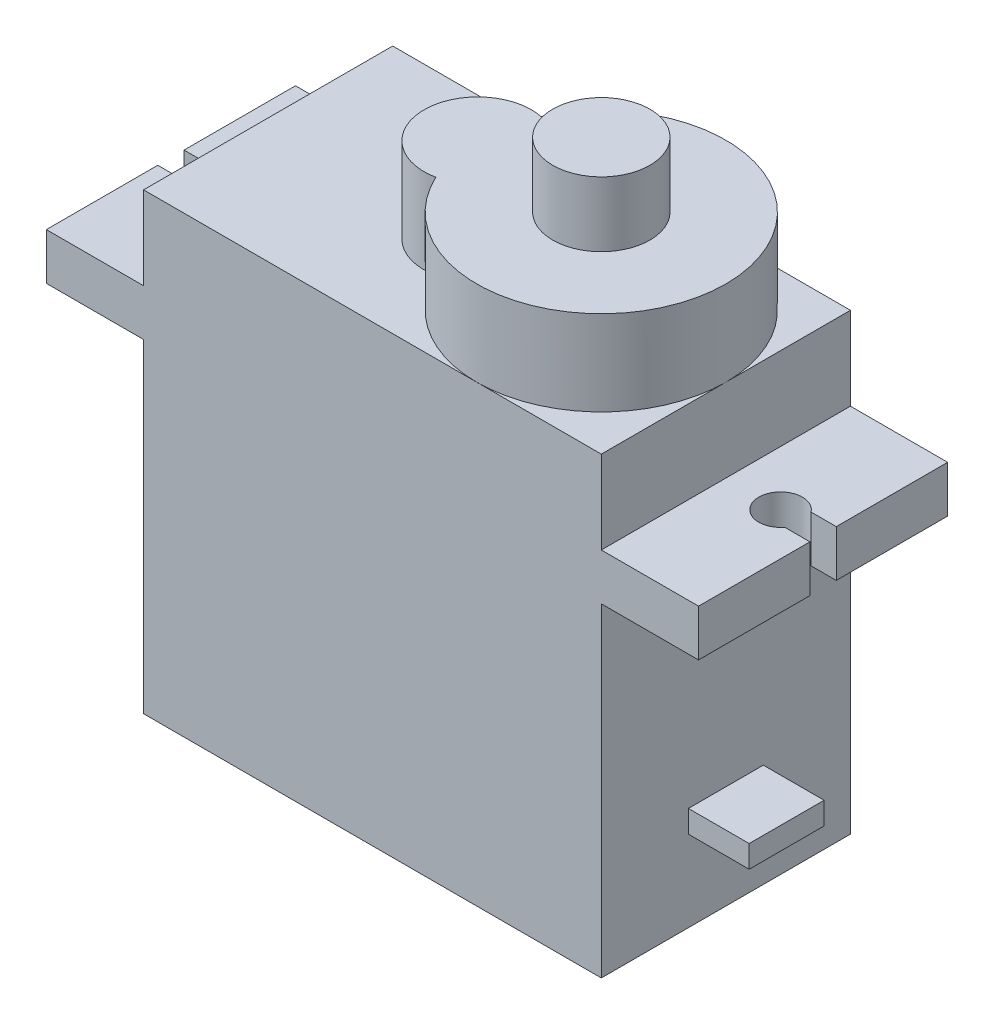
SolidWorks part; units mm, degrees
ref_plane "Plano frontal" through (0, 0, 0) normal (0, 0, 1) x (1, 0, 0)
ref_plane "Plano superior" through (0, 0, 0) normal (0, 1, 0) x (1, 0, 0)
ref_plane "Plano direito" through (0, 0, 0) normal (1, 0, 0) x (0, 0, -1)
sketch "Esboço1" plane through (0, 0, 0) normal (0, 1, 0) x (1, 0, 0)
  line L1 (-11.3, -6.15) -> (11.3, -6.15)
  line L2 (-11.3, -6.15) -> (-11.3, 6.15)
  line L3 (-11.3, 6.15) -> (11.3, 6.15)
  line L4 (11.3, -6.15) -> (11.3, 6.15)
  line L5 (-11.3, -6.15) -> (11.3, 6.15) construction
  line L6 (-11.3, 6.15) -> (11.3, -6.15) construction
  point P0 (0, 0)
  dimension "D1" = 22.6
  dimension "D2" = 12.3
extrude "Ressalto-extrusão1" add sketch "Esboço1" along normal blind 22.4
sketch "Esboço2" plane through (11.3, 0, 0) normal (1, 0, 0) x (0, 0, -1)
  line L0 (-6.15, 22.4) -> (-6.15, 0) construction
  line L1 (-6.15, 18.3) -> (6.15, 18.3)
  line L2 (-6.15, 18.3) -> (-6.15, 16)
  line L3 (-6.15, 16) -> (6.15, 16)
  line L4 (6.15, 18.3) -> (6.15, 16)
  line L5 (6.15, 22.4) -> (6.15, 0) construction
  line L6 (-6.15, 0) -> (6.15, 0) construction
  dimension "D1" = 2.3
  dimension "D2" = 16
extrude "Ressalto-extrusão2" add sketch "Esboço2" along normal blind 4.8
sketch "Esboço3" plane through (0, 18.3, 0) normal (0, 1, 0) x (1, 0, 0)
  line L0 (14.8562, 0.65) -> (16.1, 0.65)
  line L1 (16.1, 6.15) -> (16.1, -6.15) construction
  line L2 (14.8562, -0.65) -> (16.1, -0.65)
  line L3 (16.1, 0.65) -> (16.1, -0.65)
  arc A0 (14.8562, 0.65) -> (14.8562, -0.65) centre (14, 0) ccw
  dimension "D2" = 2.15
  dimension "D3" = 2.1
  dimension "D1" = 1.3
extrude "Corte-extrusão1" cut sketch "Esboço3" against normal through all
mirror "Espelhar1" about plane through (0, 0, 0) normal (1, 0, 0) of "Ressalto-extrusão2", "Corte-extrusão1"
sketch "Esboço4" plane through (0, 22.4, 0) normal (0, 1, 0) x (1, 0, 0)
  line L0 (11.3, 6.15) -> (-11.3, 6.15) construction
  line L1 (11.3, -6.15) -> (11.3, 6.15) construction
  line L2 (-11.3, 6.15) -> (-11.3, -6.15) construction
  arc A0 (-0.4246, -2.5974) -> (-0.4246, 2.5974) centre (5.15, 0) ccw
  arc A1 (-0.4246, 2.5974) -> (-0.4246, -2.5974) centre (-0.95, 0) ccw
  dimension "D1" = 5.3
  dimension "D2" = 10.35
extrude "Ressalto-extrusão3" add sketch "Esboço4" along normal blind 4.2
sketch "Esboço5" plane through (0, 26.6, 0) normal (0, 1, 0) x (1, 0, 0)
  circle A0 centre (5.15, 0) radius 2.4
  arc A1 (-0.4246, -2.5974) -> (-0.4246, 2.5974) centre (5.15, 0) ccw construction
  dimension "D1" = 4.8
extrude "Ressalto-extrusão4" add sketch "Esboço5" along normal blind 3.2
sketch "Esboço6" plane through (11.3, 0, 0) normal (1, 0, 0) x (0, 0, -1)
  line L0 (-6.15, 0) -> (6.15, 0) construction
  line L1 (-1.85, 5.1) -> (1.85, 5.1)
  line L2 (-1.85, 5.1) -> (-1.85, 4)
  line L3 (-1.85, 4) -> (1.85, 4)
  line L4 (1.85, 5.1) -> (1.85, 4)
  point P6 (0, 4)
  dimension "D1" = 3.7
  dimension "D2" = 1.1
  dimension "D3" = 4
extrude "Ressalto-extrusão5" add sketch "Esboço6" along normal blind 3
ref_point "Ponto1"
ref_point "Ponto2"
sketch "Esboço7" plane through (0, 0, 0) normal (0, -1, 0) x (1, 0, 0)
  line L0 (11.3, 6.15) -> (11.3, -6.15) construction
  line L1 (-11.3, -6.15) -> (-11.3, 6.15) construction
  point P0 (5.15, 0)
  dimension "D1" = 6.15
  dimension "D2" = 16.45
sketch "Esboço9" plane through (0, 0, 0) normal (0, 1, 0) x (1, 0, 0)
  arc A0 (-14.8562, -0.65) -> (-14.8562, 0.65) centre (-14, 0) ccw construction
  arc A1 (14.8562, 0.65) -> (14.8562, -0.65) centre (14, 0) ccw construction
  point P0 (-14, 0)
  point P1 (14, 0)
  point P10 (5.15, 0)
  dimension "D1" = 19.15
  dimension "D2" = 8.85
  dimension "D3" = 28
